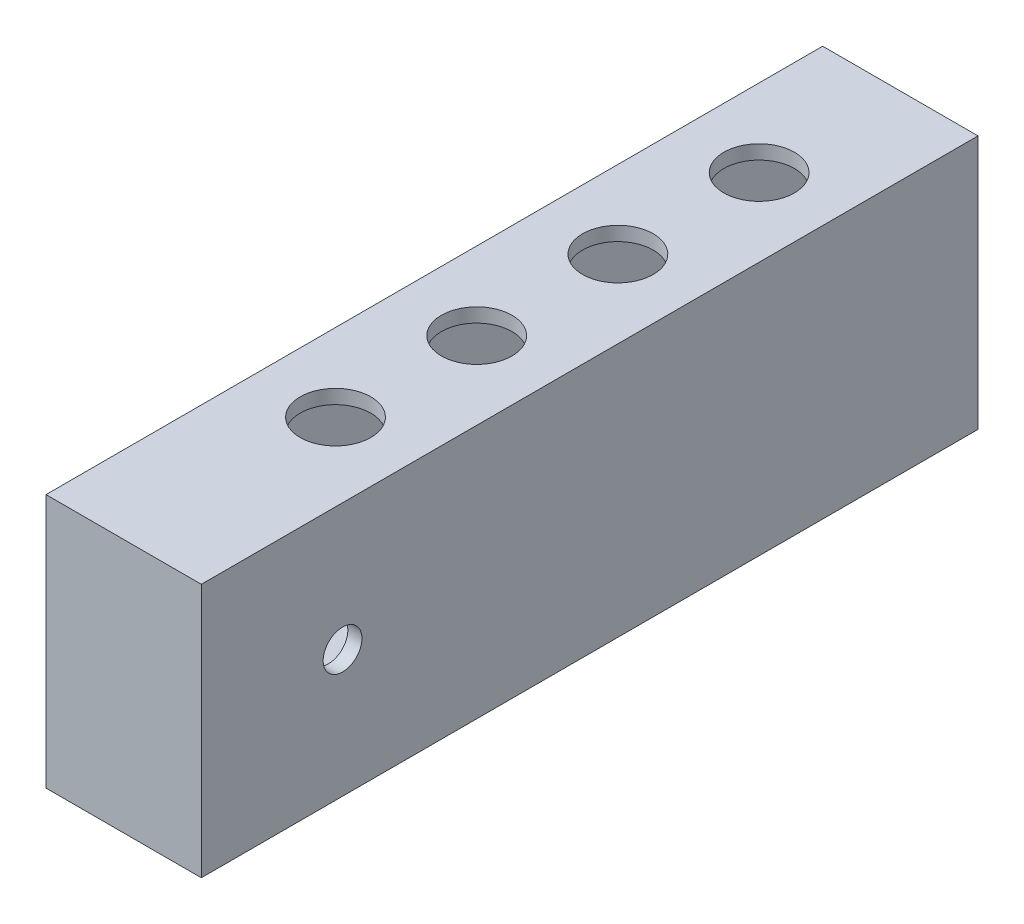
SolidWorks part; units mm, degrees
ref_plane "Plano frontal" through (0, 0, 0) normal (0, 0, 1) x (1, 0, 0)
ref_plane "Plano superior" through (0, 0, 0) normal (0, 1, 0) x (1, 0, 0)
ref_plane "Plano direito" through (0, 0, 0) normal (1, 0, 0) x (0, 0, -1)
sketch "Esboço1" plane through (0, 0, 0) normal (0, 0, 1) x (1, 0, 0)
  line L0 (0, 0) -> (11, 0)
  line L1 (11, 0) -> (11, 36)
  line L2 (11, 36) -> (-11, 36)
  line L3 (-11, 36) -> (-11, 0)
  line L4 (-11, 0) -> (0, 0)
  line L5 (0, 36) -> (0, 0)
  line L7 (-9, 2) -> (9, 2)
  line L8 (-9, 2) -> (-9, 34)
  line L9 (-9, 34) -> (9, 34)
  line L10 (9, 2) -> (9, 34)
  line L11 (-9, 2) -> (9, 34) construction
  line L12 (-9, 34) -> (9, 2) construction
  point P7 (0, 18)
  dimension "D1" = 11
  dimension "D2" = 36
  dimension "D3" = 22
  dimension "D4" = 32
  dimension "D5" = 18
extrude "Ressalto-extrusão1" add sketch "Esboço1" along normal blind 110 contours L10 L7 L5 L0 L1 L2 L9 | L8 L9 L5 L2 L3 L4 L7
shell "Casca1" thickness 2
sketch "Esboço2" plane through (0, 0, 0) normal (0, -1, 0) x (-1, 0, 0)
  line L0 (0, 0) -> (0, -20)
  circle A0 centre (0, -20) radius 5
  circle A1 centre (0, -40) radius 5
  circle A2 centre (0, -60) radius 5
  circle A3 centre (0, -80) radius 5
  circle A5 centre (0, -100) radius 5 [skipped]
  dimension "D2" = 10
  dimension "D1" = 20
  dimension "D3" = 5
extrude "Corte-extrusão1" cut sketch "Esboço2" against normal blind 1000
sketch "Esboço3" plane through (11, 0, 0) normal (1, 0, 0) x (0, 0, -1)
  line L0 (-110, 18) -> (-90, 18)
  line L1 (-110, 0) -> (-110, 36) construction
  circle A0 centre (-90, 18) radius 2.75
  dimension "D2" = 5.5
  dimension "D1" = 20
extrude "Corte-extrusão2" cut sketch "Esboço3" against normal blind 29 contours A0
